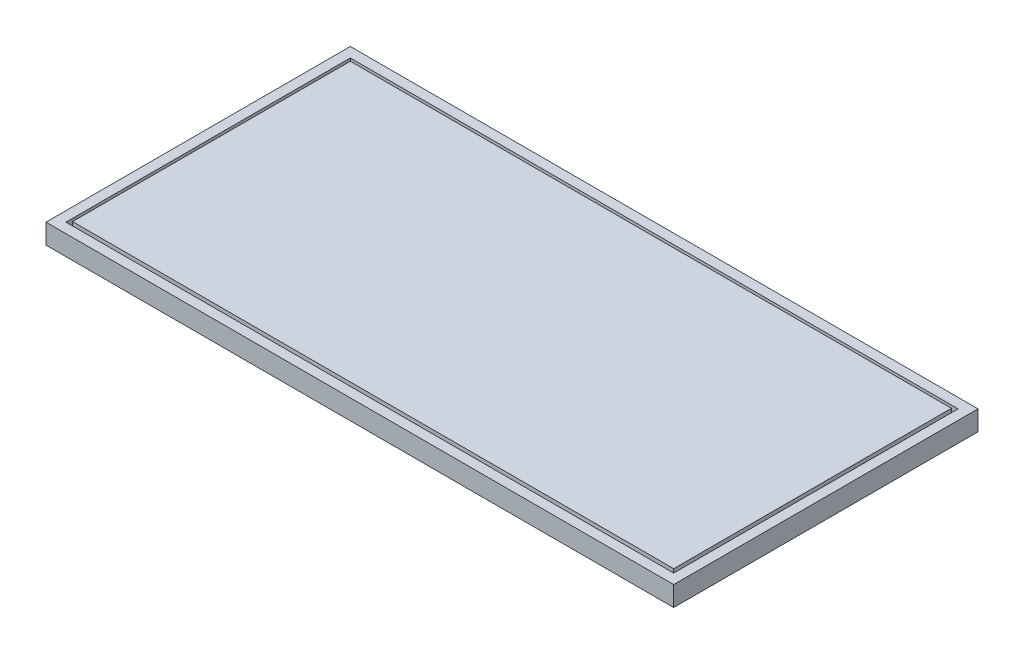
SolidWorks part; units mm, degrees
ref_plane "Front" through (0, 0, 0) normal (0, 0, 1) x (1, 0, 0)
ref_plane "Top" through (0, 0, 0) normal (0, 1, 0) x (1, 0, 0)
ref_plane "Right" through (0, 0, 0) normal (1, 0, 0) x (0, 0, -1)
sketch "Sketch1" plane through (0, 0, 0) normal (0, 1, 0) x (1, 0, 0)
  line L1 (-46.0375, 21.2725) -> (46.0375, 21.2725)
  line L2 (-46.0375, 21.2725) -> (-46.0375, -21.2725)
  line L3 (-46.0375, -21.2725) -> (46.0375, -21.2725)
  line L4 (46.0375, 21.2725) -> (46.0375, -21.2725)
  line L5 (-46.0375, 21.2725) -> (46.0375, -21.2725) construction
  line L6 (-46.0375, -21.2725) -> (46.0375, 21.2725) construction
  point P0 (0, 0)
  dimension "D1" = 92.075
  dimension "D2" = 42.545
extrude "Boss-Extrude2" add sketch "Sketch1" along normal blind 1.6
sketch "Sketch2" plane through (0, 0, 0) normal (0, -1, 0) x (1, 0, 0)
  line L0 (46.5455, 21.7805) -> (-46.5455, 21.7805)
  line L1 (-46.5455, 21.7805) -> (-46.5455, -21.7805)
  line L2 (-46.5455, -21.7805) -> (46.5455, -21.7805)
  line L3 (46.5455, -21.7805) -> (46.5455, 21.7805)
  line L4 (46.0375, -21.2725) -> (46.0375, 21.2725)
  line L5 (46.0375, 21.2725) -> (-46.0375, 21.2725)
  line L6 (-46.0375, 21.2725) -> (-46.0375, -21.2725)
  line L7 (-46.0375, -21.2725) -> (46.0375, -21.2725)
  line L8 (46.0375, -21.2725) -> (46.0375, 21.2725)
  line L9 (46.0375, 21.2725) -> (-46.0375, 21.2725)
  line L10 (-46.0375, 21.2725) -> (-46.0375, -21.2725)
  line L11 (-46.0375, -21.2725) -> (46.0375, -21.2725)
  line L12 (48.0695, 23.3045) -> (-48.0695, 23.3045)
  line L13 (-48.0695, 23.3045) -> (-48.0695, -23.3045)
  line L14 (-48.0695, -23.3045) -> (48.0695, -23.3045)
  line L15 (48.0695, -23.3045) -> (48.0695, 23.3045)
  dimension "D1" = 0
  dimension "D2" = 0.508
  dimension "D3" = 1.524
extrude "Boss-Extrude4" add sketch "Sketch2" along normal blind 1.524 and the other way blind 1.524 separate body contours L14 L15 L12 L13 L3 L2 L1 L0
